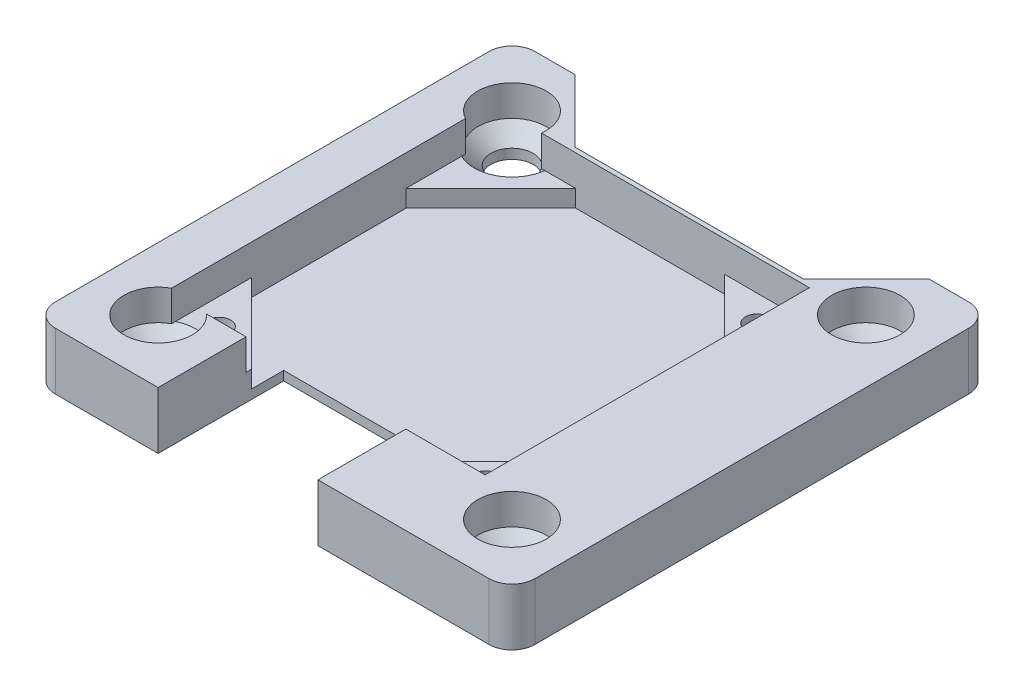
SolidWorks part; units mm, degrees
ref_plane "前视基准面" through (0, 0, 0) normal (0, 0, 1) x (1, 0, 0)
ref_plane "上视基准面" through (0, 0, 0) normal (0, 1, 0) x (1, 0, 0)
ref_plane "右视基准面" through (0, 0, 0) normal (1, 0, 0) x (0, 0, -1)
sketch "草图1" plane through (0, 0, 0) normal (0, 1, 0) x (1, 0, 0)
  line L1 (-21, -21) -> (21, -21)
  line L2 (-21, -21) -> (-21, 21)
  line L3 (-21, 21) -> (21, 21)
  line L4 (21, -21) -> (21, 21)
  line L5 (-21, -21) -> (21, 21) construction
  line L6 (-21, 21) -> (21, -21) construction
  line L7 (-15.5, -15.5) -> (15.5, -15.5) construction
  line L8 (-15.5, -15.5) -> (-15.5, 15.5) construction
  line L9 (-15.5, 15.5) -> (15.5, 15.5) construction
  line L10 (15.5, -15.5) -> (15.5, 15.5) construction
  line L11 (-15.5, -15.5) -> (15.5, 15.5) construction
  line L12 (-15.5, 15.5) -> (15.5, -15.5) construction
  circle A0 centre (15.5, 15.5) radius 1.85
  circle A1 centre (-15.5, 15.5) radius 1.85
  circle A2 centre (-15.5, -15.5) radius 1.85
  circle A3 centre (15.5, -15.5) radius 1.85
  point P0 (0, 0)
  point P6 (0, 0)
  dimension "D3" = 3.7
  dimension "D1" = 42
  dimension "D2" = 31
extrude "凸台-拉伸1" add sketch "草图1" along normal blind 5
fillet "圆角2" radius 2 1 edges at (-21, 2.5, -21)
fillet "圆角3" radius 2 1 edges at (-21, 2.5, 21)
fillet "圆角4" radius 2 1 edges at (21, 2.5, 21)
fillet "圆角5" radius 2 1 edges at (21, 2.5, -21)
sketch "草图2" plane through (0, 0, 0) normal (0, -1, 0) x (1, 0, 0)
  line L0 (21, 19) -> (21, -19) construction
  line L1 (21, 12.95) -> (17, 12.95)
  line L2 (21, 12.95) -> (21, 2.45)
  line L3 (21, 2.45) -> (17, 2.45)
  line L4 (17, 12.95) -> (17, 2.45)
  line L5 (-21, -19) -> (-21, 19) construction
  line L6 (-19, 21) -> (19, 21) construction
  line L7 (-21, 12.77) -> (-17, 12.77)
  line L8 (-21, 12.77) -> (-21, -13.23)
  line L9 (-21, -13.23) -> (-17, -13.23)
  line L10 (-17, 12.77) -> (-17, -13.23)
  line L11 (19, -21) -> (-19, -21) construction
  line L12 (21, -12.135) -> (8, -12.135)
  line L13 (21, -12.135) -> (21, -7.135)
  line L14 (21, -7.135) -> (8, -7.135)
  line L15 (8, -12.135) -> (8, -7.135)
  point P6 (21, 7.7)
  point P15 (-21, -0.23)
  point P20 (21, -9.635)
  dimension "D1" = 13.3
  dimension "D2" = 4
  dimension "D3" = 10.5
  dimension "D4" = 21.23
  dimension "D5" = 26
  dimension "D6" = 4
  dimension "D7" = 13
  dimension "D8" = 5
  dimension "D9" = 11.365
extrude "切除-拉伸1" [suppressed] cut sketch "草图2" against normal blind 6
sketch "草图3" plane through (0, 0, 0) normal (0, -1, 0) x (1, 0, 0)
  line L0 (21, 19) -> (21, -19) construction
  line L1 (21, -7.5) -> (15.442, -7.5)
  line L2 (21, -7.5) -> (21, 1.5)
  line L3 (21, 1.5) -> (15.442, 1.5)
  line L4 (15.442, -7.5) -> (15.442, 1.5)
  line L5 (19, -21) -> (-19, -21) construction
  point P6 (21, -3)
  dimension "D1" = 18
  dimension "D2" = 9
extrude "切除-拉伸2" [suppressed] cut sketch "草图3" against normal blind 3
sketch "草图5" plane through (0, 0, 0) normal (0, -1, 0) x (1, 0, 0)
  line L0 (-15.5, -21) -> (-10, -15.5)
  line L1 (19, -21) -> (-19, -21) construction
  line L2 (15.5, -21) -> (10, -15.5)
  line L3 (10, -15.5) -> (-10, -15.5)
  line L4 (-15.5, -21) -> (15.5, -21)
extrude "切除-拉伸3" cut sketch "草图5" against normal through all
sketch "草图10" plane through (0, 5, 0) normal (0, 1, 0) x (1, 0, 0)
  line L0 (21, -19) -> (21, 19) construction
  line L1 (-19, -21) -> (19, -21) construction
  circle A0 centre (7, -17) radius 4.5
  dimension "D1" = 9
  dimension "D2" = 14
  dimension "D3" = 4
extrude "切除-拉伸13" [suppressed] cut sketch "草图10" against normal through all
sketch "草图6" plane through (0, 0, 0) normal (0, -1, 0) x (1, 0, 0)
  line L1 (-19, 21) -> (19, 21) construction
  line L2 (-10, 21) -> (4, 21)
  line L3 (-10, 21) -> (-10, 10)
  line L4 (-10, 10) -> (4, 10)
  line L6 (4, 21) -> (4, 10)
  line L7 (-21, -19) -> (-21, 19) construction
  line L8 (21, 19) -> (21, -19) construction
  dimension "D1" = 11
  dimension "D2" = 17
  dimension "D3" = 11
extrude "切除-拉伸4" cut sketch "草图6" against normal through all
sketch "草图7" plane through (0, 0, 0) normal (0, -1, 0) x (1, 0, 0)
  line L0 (-9.0163, 15.5) -> (-15.5, 9.0163)
  line L1 (-15.5, 15.5) -> (15.5, 15.5) construction
  line L2 (-15.5, 15.5) -> (-15.5, -15.5) construction
  line L3 (-15.5, -15.5) -> (15.5, -15.5) construction
  line L4 (15.5, 15.5) -> (15.5, -15.5) construction
  line L5 (-15.5, 9.0163) -> (-15.5, -9.0163)
  line L6 (-15.5, -9.0163) -> (-9.0163, -15.5)
  line L7 (-9.0163, -15.5) -> (9.0163, -15.5)
  line L8 (9.0163, -15.5) -> (15.5, -9.0163)
  line L9 (15.5, -9.0163) -> (15.5, 9.0163)
  line L10 (15.5, 9.0163) -> (9.0163, 15.5)
  line L11 (9.0163, 15.5) -> (-9.0163, 15.5)
extrude "切除-拉伸5" [suppressed] cut sketch "草图7" against normal blind 3
sketch "草图8" plane through (0, 5, 0) normal (0, 1, 0) x (1, 0, 0)
  line L0 (-21, 19) -> (-21, -19) construction
  line L1 (-8.5, -10.5) -> (2.5, -10.5) construction
  line L2 (-8.5, -10.5) -> (-8.5, -12.5) construction
  line L3 (-8.5, -12.5) -> (2.5, -12.5) construction
  line L4 (2.5, -10.5) -> (2.5, -12.5) construction
  line L5 (-19, -21) -> (-10, -21) construction
  line L6 (-3, -12.5) -> (-3, -10.5) construction
  line L7 (2.5, -11.5) -> (-8.5, -11.5) construction
  circle A0 centre (-14.65, -11) radius 1
  circle A1 centre (8.65, -11) radius 1
  circle A2 centre (-14.65, 12.8) radius 1 construction
  circle A3 centre (8.65, 12.8) radius 1
  point P4 (-3, -10.5)
  point P7 (-8.5, -11.5)
  dimension "D4" = 2
  dimension "D5" = 23.3
  dimension "D6" = 23.8
  dimension "D1" = 18
  dimension "D2" = 9.5
  dimension "D3" = 11
  dimension "D7" = 2
  dimension "D8" = 0.5
extrude "切除-拉伸6" cut sketch "草图8" against normal through all
sketch "草图9" plane through (0, 5, 0) normal (0, 1, 0) x (1, 0, 0)
  circle A0 centre (-15.5, 15.5) radius 3
  circle A1 centre (15.5, 15.5) radius 3
  circle A2 centre (15.5, -15.5) radius 3
  circle A3 centre (-15.5, -15.5) radius 3
  dimension "D1" = 6
extrude "切除-拉伸7" cut sketch "草图9" against normal blind 2.7
sketch "草图11" plane through (0, 5, 0) normal (0, 1, 0) x (1, 0, 0)
  line L1 (10.95, -13.3) -> (-16.95, -13.3)
  line L2 (10.95, -13.3) -> (10.95, 15.1)
  line L3 (10.95, 15.1) -> (-16.95, 15.1)
  line L4 (-16.95, -13.3) -> (-16.95, 15.1)
  circle A1 centre (-14.65, -11) radius 1 construction
  circle A3 centre (8.65, 12.8) radius 1 construction
  dimension "D1" = 2.3
  dimension "D2" = 2.3
  dimension "D3" = 2.3
  dimension "D4" = 2.3
extrude "切除-拉伸14" cut sketch "草图11" against normal up to surface (2.7 mm away) up to face at (15.5, 2.3, 17.35)
sketch "草图12" plane through (0, 2.3, 0) normal (0, 1, 0) x (1, 0, 0)
  line L0 (10.95, -5.8716) -> (10.95, 7.6716)
  line L1 (10.95, -13.3) -> (10.95, 15.1) construction
  line L2 (10.95, 7.6716) -> (3.5216, 15.1)
  line L3 (10.95, 15.1) -> (-12.5268, 15.1) construction
  line L4 (3.5216, 15.1) -> (-9.5216, 15.1)
  line L5 (-9.5216, 15.1) -> (-16.95, 7.6716)
  line L6 (-16.95, 12.8737) -> (-16.95, -12.8737) construction
  line L7 (-16.95, 7.6716) -> (-16.95, -5.8716)
  line L8 (-16.95, -5.8716) -> (-9.5216, -13.3)
  line L9 (-13.4604, -13.3) -> (-10, -13.3) construction
  line L10 (-9.5216, -13.3) -> (3.5216, -13.3)
  line L11 (4, -13.3) -> (10.95, -13.3) construction
  line L12 (3.5216, -13.3) -> (10.95, -5.8716)
  circle A0 centre (8.65, -11) radius 1 construction
  dimension "D1" = 2
  dimension "D2" = 135
extrude "切除-拉伸15" cut sketch "草图12" against normal blind 1.5
hole_wizard "打孔尺寸(%根据十字)槽半沉头木螺钉的类型1" positions "草图13" profile "草图14" size "M3" standard "GB" slot yes end condition up to next
sketch "草图13" plane through (0, 2.3, 0) normal (0, 1, 0) x (1, 0, 0)
  point P0 (15.5, -15.5)
  point P3 (-15.5, -15.5)
  point P6 (-15.5, 15.5)
  point P9 (15.5, 15.5)
sketch "草图14" plane through (15.5, 2.3, 15.5) normal (1, 0, 0) x (0, 0, 1)
  line L0 (0, 0) -> (0, 2.3)
  line L1 (0, 2.3) -> (1.8, 2.3)
  line L2 (1.8, 2.3) -> (1.8, 1.5)
  line L3 (1.8, 1.5) -> (3.3, 0)
  line L5 (3.3, 0) -> (0, 0)
  line L6 (-1.8, 1.5) -> (-3.3, 0) construction
  line L11 (0, -6.35) -> (0, 107.95) construction
  dimension "通孔孔直径" = 3.6
  dimension "通孔孔深度" = 2.3
  dimension "近端锥形沉头孔直径" = 6.6
  dimension "近端锥形沉头孔角度" = 90
